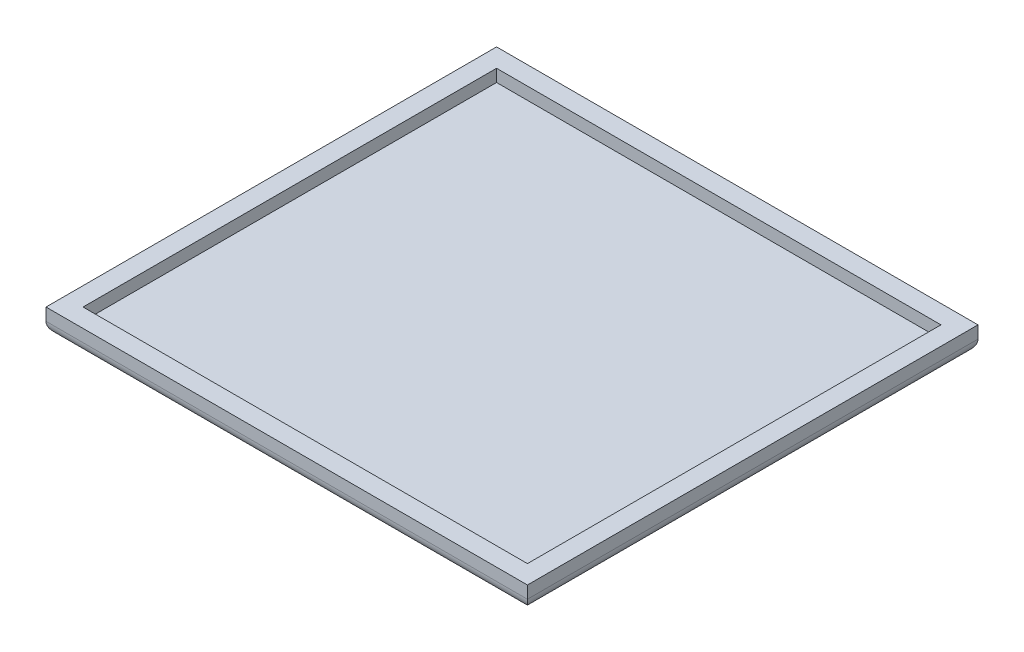
SolidWorks part; units mm, degrees
ref_plane "Front Plane" through (0, 0, 0) normal (0, 0, 1) x (1, 0, 0)
ref_plane "Top Plane" through (0, 0, 0) normal (0, 1, 0) x (1, 0, 0)
ref_plane "Right Plane" through (0, 0, 0) normal (1, 0, 0) x (0, 0, -1)
sketch "Sketch2" plane through (0, 0, 0) normal (0, 1, 0) x (1, 0, 0)
  line L1 (0, 0) -> (78, 0)
  line L2 (0, 0) -> (0, 73)
  line L3 (0, 73) -> (78, 73)
  line L4 (78, 0) -> (78, 73)
  dimension "D1" = 78
  dimension "D2" = 73
extrude "Boss-Extrude1" add sketch "Sketch2" along normal blind 4
sketch "Sketch3" plane through (0, 4, 0) normal (0, 1, 0) x (1, 0, 0)
  line L0 (78, 73) -> (0, 73) construction
  line L1 (3, 70) -> (75, 70)
  line L2 (3, 70) -> (3, 3)
  line L3 (3, 3) -> (75, 3)
  line L4 (75, 70) -> (75, 3)
  line L5 (78, 0) -> (78, 73) construction
  line L6 (0, 0) -> (78, 0) construction
  line L7 (0, 73) -> (0, 0) construction
  dimension "D1" = 3
  dimension "D2" = 3
  dimension "D3" = 3
  dimension "D4" = 3
extrude "Cut-Extrude1" cut sketch "Sketch3" against normal blind 2 contours L3 L4 L1 L2
fillet "Fillet1" radius 2 4 edges at (0, 0, -36.5) (39, 0, 0) (78, 0, -36.5) (39, 0, -73)
